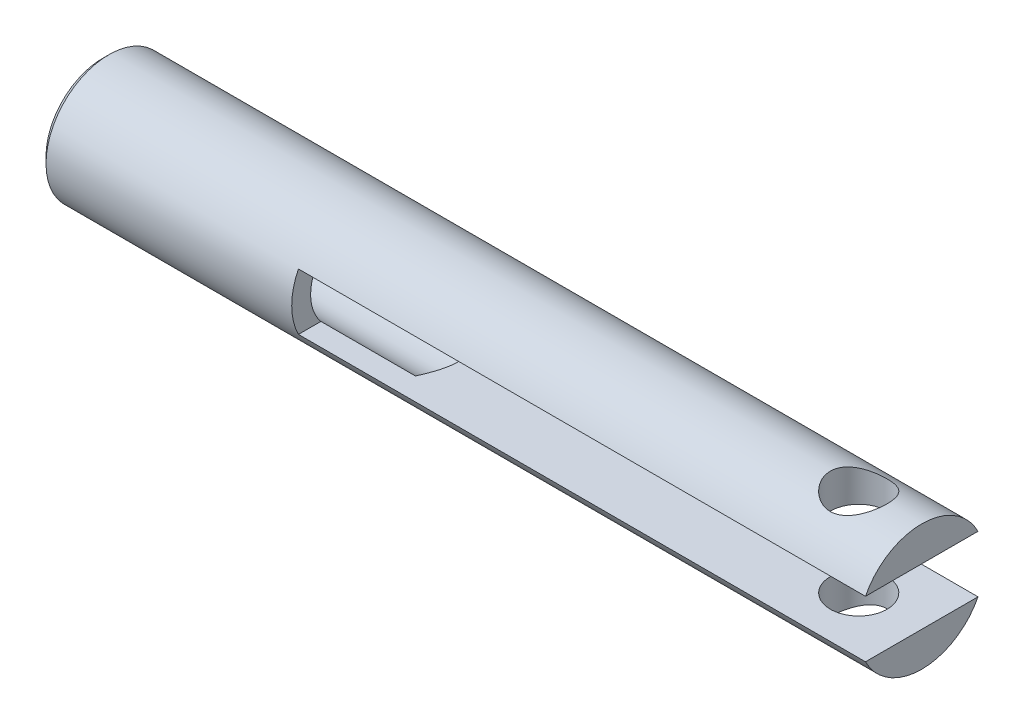
SolidWorks part; units mm, degrees
ref_plane "Plan1" through (0, 0, 0) normal (0, 0, 1) x (1, 0, 0)
ref_plane "Plan2" through (0, 0, 0) normal (0, 1, 0) x (1, 0, 0)
ref_plane "Plan3" through (0, 0, 0) normal (1, 0, 0) x (0, 0, -1)
sketch "Esquisse1" plane through (0, 0, 0) normal (0, 0, 1) x (1, 0, 0)
  line L0 (0, 7) -> (0, 9)
  line L1 (1, 10) -> (130, 10)
  line L2 (130, 10) -> (130, 0)
  line L3 (1, 10) -> (0, 9)
  line L6 (130, 0) -> (59.0415, 0)
  line L7 (59.0415, 0) -> (55, 7)
  line L8 (55, 7) -> (0, 7)
  line L9 (0, 0) -> (126, 0) construction
  dimension "D1" = 130
  dimension "D2" = 45
  dimension "D3" = 1
  dimension "D4" = 10
  dimension "D7" = 14
  dimension "D8" = 55
  dimension "D9" = 60
revolve "Base-Révolution" add sketch "Esquisse1" angle 360 about L9
ref_plane "Plan4" through (0, 10, 0) normal (0, 1, 0) x (-1, 0, 0)
sketch "Esquisse2" plane through (0, 10, 0) normal (0, 1, 0) x (-1, 0, 0)
  circle A0 centre (-120, 0) radius 4.5
  dimension "D1" = 9
  dimension "D2" = 120
extrude "Enlèv. mat.-Extru.1" cut sketch "Esquisse2" against normal through all
sketch "Esquisse3" plane through (0, 0, 0) normal (0, 1, 0) x (1, 0, 0)
  line L0 (130, -10) -> (130, 10) construction
  line L1 (130, 10) -> (40, 10)
  line L2 (130, 10) -> (130, -10)
  line L3 (130, -10) -> (40, -10)
  line L4 (40, 10) -> (40, -10)
  line L5 (130, 10) -> (1, 10) construction
  dimension "D1" = 20
  dimension "D2" = 90
extrude "Enlèv. mat.-Extru.2" cut sketch "Esquisse3" against normal mid plane 9
